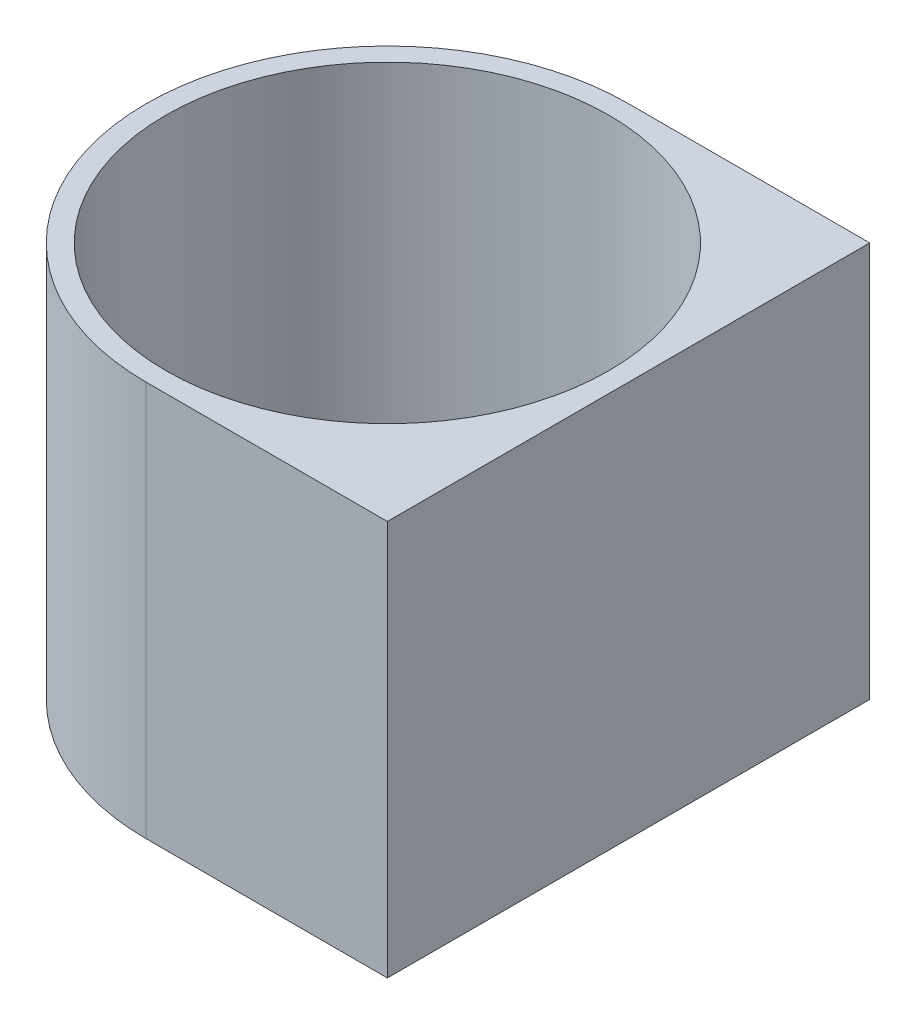
SolidWorks part; units mm, degrees
ref_plane "Front Plane" through (0, 0, 0) normal (0, 0, 1) x (1, 0, 0)
ref_plane "Top Plane" through (0, 0, 0) normal (0, 1, 0) x (1, 0, 0)
ref_plane "Right Plane" through (0, 0, 0) normal (1, 0, 0) x (0, 0, -1)
sketch "Sketch1" plane through (0, 0, 0) normal (0, 1, 0) x (1, 0, 0)
  circle A0 centre (0, 0) radius 38.735
  circle A1 centre (0, 0) radius 35.56
  dimension "D1" = 71.12
  dimension "D2" = 3.175
extrude "Boss-Extrude1" add sketch "Sketch1" along normal blind 63.5
ref_plane "Plane1" through (38.735, 0, 0) normal (1, 0, 0) x (0, 0, -1)
sketch "Sketch2" plane through (38.735, 0, 0) normal (1, 0, 0) x (0, 0, -1)
  line L1 (-38.735, 63.5) -> (38.735, 63.5)
  line L2 (-38.735, 63.5) -> (-38.735, 0)
  line L3 (-38.735, 0) -> (38.735, 0)
  line L4 (38.735, 63.5) -> (38.735, 0)
extrude "Boss-Extrude2" add sketch "Sketch2" against normal up to surface (38.735 mm away) up to face at (0, 63.5, 38.735)
sketch "Sketch3" plane through (38.735, 0, 0) normal (1, 0, 0) x (0, 0, -1)
  line L0 (-44.45, 0) -> (44.45, 0)
  line L1 (44.45, 0) -> (44.45, 82.55)
  line L2 (44.45, 82.55) -> (38.1, 82.55)
  line L3 (38.1, 82.55) -> (38.1, 63.5)
  line L4 (38.1, 63.5) -> (21.59, 63.5)
  line L5 (21.59, 63.5) -> (21.59, 3.175)
  line L6 (21.59, 3.175) -> (-21.59, 3.175)
  line L7 (-21.59, 3.175) -> (-21.59, 63.5)
  line L8 (-21.59, 63.5) -> (-38.1, 63.5)
  line L9 (-38.1, 63.5) -> (-38.1, 82.55)
  line L10 (-38.1, 82.55) -> (-44.45, 82.55)
  line L11 (-44.45, 82.55) -> (-44.45, 0)
  point P2 (-17.6674, 54.6866)
  point P13 (0, 0)
  dimension "D1" = 88.9
  dimension "D2" = 6.35
  dimension "D3" = 43.18
  dimension "D4" = 19.05
  dimension "D5" = 60.325
  dimension "D6" = 3.175
